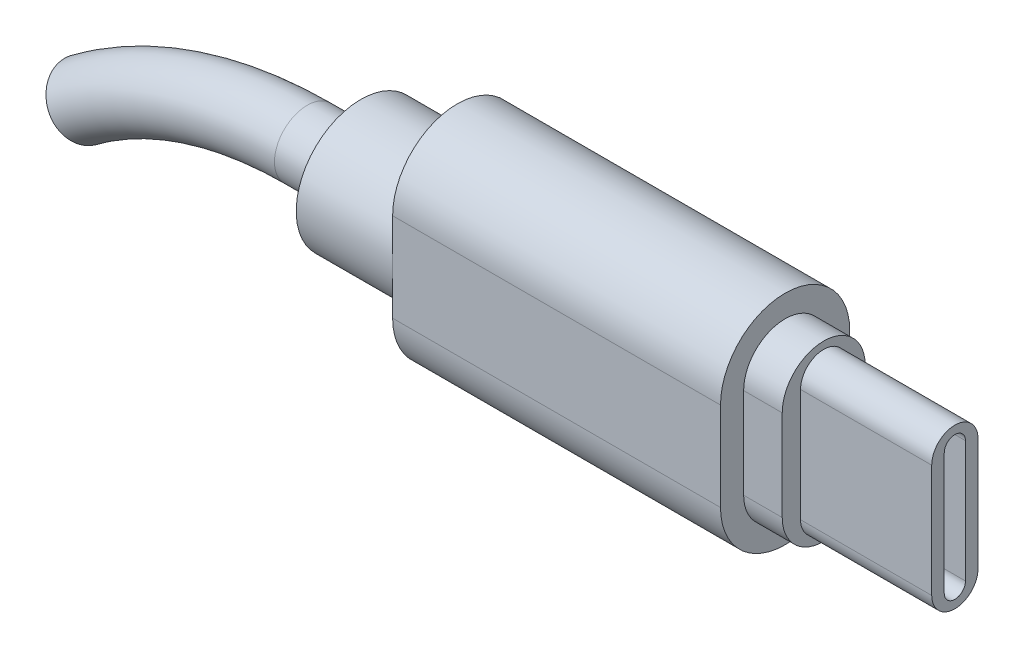
SolidWorks part; units mm, degrees
ref_plane "Front" through (0, 0, 0) normal (0, 0, 1) x (1, 0, 0)
ref_plane "Top" through (0, 0, 0) normal (0, 1, 0) x (1, 0, 0)
ref_plane "Right" through (0, 0, 0) normal (1, 0, 0) x (0, 0, -1)
sketch "Эскиз1" plane through (0, 0, 0) normal (1, 0, 0) x (0, 0, -1)
  line L0 (0, -2.3) -> (0, 2.3) construction
  line L1 (-3.35, -2.3) -> (-3.35, 2.3)
  line L2 (3.35, -2.3) -> (3.35, 2.3)
  arc A0 (-3.35, -2.3) -> (3.35, -2.3) centre (0, -2.3) ccw
  arc A1 (3.35, 2.3) -> (-3.35, 2.3) centre (0, 2.3) ccw
  point P2 (0, 0)
  point P8 (0, -5.65)
  point P9 (0, 5.65)
  dimension "D1" = 6.7
  dimension "D2" = 11.3
extrude "Бобышка-Вытянуть1" add sketch "Эскиз1" against normal blind 17
sketch "Эскиз3" plane through (0, 0, 0) normal (-1, 0, 0) x (0, 0, 1)
  line L0 (0, 2.35) -> (0, -2.35) construction
  line L1 (2.15, 2.35) -> (2.15, -2.35)
  line L2 (-2.15, 2.35) -> (-2.15, -2.35)
  arc A0 (2.15, 2.35) -> (-2.15, 2.35) centre (0, 2.35) ccw
  arc A1 (-2.15, -2.35) -> (2.15, -2.35) centre (0, -2.35) ccw
  point P2 (0, 0)
  point P8 (0, -4.5)
  point P9 (0, 4.5)
  dimension "D1" = 4.3
  dimension "D2" = 9
extrude "Бобышка-Вытянуть2" add sketch "Эскиз3" against normal blind 2
sketch "Эскиз4" plane through (-17, 0, 0) normal (1, 0, 0) x (0, 0, -1)
  line L1 (3.35, -2.3) -> (3.35, 2.3) construction
  circle A0 centre (0, 0) radius 3.35
extrude "Бобышка-Вытянуть3" add sketch "Эскиз4" against normal blind 5
sketch "Эскиз5" plane through (-22, 0, 0) normal (-1, 0, 0) x (0, 0, 1)
  circle A0 centre (0, 0) radius 1.7
  dimension "D1" = 3.4
sketch "Эскиз6" plane through (0, 0, 0) normal (0, 0, 1) x (1, 0, 0)
  line L0 (-22, 0) -> (-24.7762, 0)
  line L1 (-22, 1.7) -> (-22, -1.7) construction
  arc A0 (-24.7762, 0) -> (-36.3422, -3.8456) centre (-24.7762, -19.3158) ccw
sweep "По траектории1" add profiles "Эскиз5" path "Эскиз6"
sketch "Эскиз7" plane through (2, 0, 0) normal (1, 0, 0) x (0, 0, -1)
  line L5 (0, -2.925) -> (0, 2.925) construction
  line L6 (-1.2, -2.925) -> (-1.2, 2.925)
  line L8 (1.2, -2.925) -> (1.2, 2.925)
  arc A0 (-1.2, -2.925) -> (1.2, -2.925) centre (0, -2.925) ccw
  arc A1 (1.2, 2.925) -> (-1.2, 2.925) centre (0, 2.925) ccw
  point P2 (0, 0)
  point P7 (0, 4.125)
  point P8 (0, -4.125)
  dimension "D1" = 8.25
  dimension "D2" = 2.4
extrude "Бобышка-Вытянуть4" add sketch "Эскиз7" along normal blind 6.8
sketch "Эскиз8" plane through (8.8, 0, -8.8) normal (-1, 0, 0) x (0, 0, 1)
  line L9 (8.8, -3.15) -> (8.8, 3.15) construction
  line L10 (8.25, -3.15) -> (8.25, 3.15)
  line L11 (9.35, -3.15) -> (9.35, 3.15)
  arc A2 (8.25, -3.15) -> (9.35, -3.15) centre (8.8, -3.15) ccw
  arc A3 (9.35, 3.15) -> (8.25, 3.15) centre (8.8, 3.15) ccw
  point P11 (8.8, 0)
  dimension "D3" = 0.55
  dimension "D4" = 6.3
extrude "Вырез-Вытянуть1" cut sketch "Эскиз8" along normal blind 5
